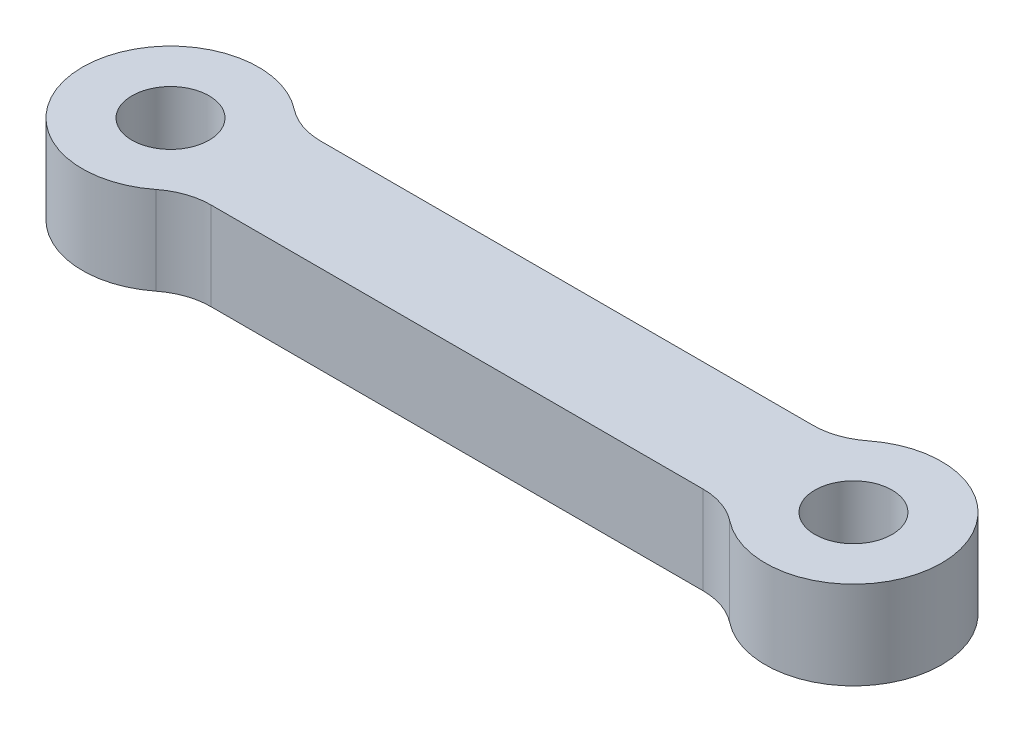
SolidWorks part; units mm, degrees
ref_plane "Front Plane" through (0, 0, 0) normal (0, 0, 1) x (1, 0, 0)
ref_plane "Top Plane" through (0, 0, 0) normal (0, 1, 0) x (1, 0, 0)
ref_plane "Right Plane" through (0, 0, 0) normal (1, 0, 0) x (0, 0, -1)
ref_plane "Plane1" through (0, 0, 0) normal (0, -1, 0) x (1, 0, 0)
sketch "Sketch1" plane through (0, 0, 0) normal (0, -1, 0) x (1, 0, 0)
  line L0 (26.6699, 2.5) -> (4.3301, 2.5)
  line L1 (4.3301, -2.5) -> (26.6699, -2.5)
  circle A0 centre (31, 0) radius 1.75
  circle A1 centre (0, 0) radius 1.75
  arc A2 (28.5256, 3.1429) -> (26.6699, 2.5) centre (26.6699, 5.5) cw
  arc A3 (4.3301, 2.5) -> (2.4744, 3.1429) centre (4.3301, 5.5) cw
  arc A4 (2.4744, 3.1429) -> (2.4744, -3.1429) centre (0, 0) ccw
  arc A5 (2.4744, -3.1429) -> (4.3301, -2.5) centre (4.3301, -5.5) cw
  arc A6 (26.6699, -2.5) -> (28.5256, -3.1429) centre (26.6699, -5.5) cw
  arc A7 (28.5256, -3.1429) -> (28.5256, 3.1429) centre (31, 0) ccw
extrude "Boss-Extrude1" add sketch "Sketch1" against normal blind 4
